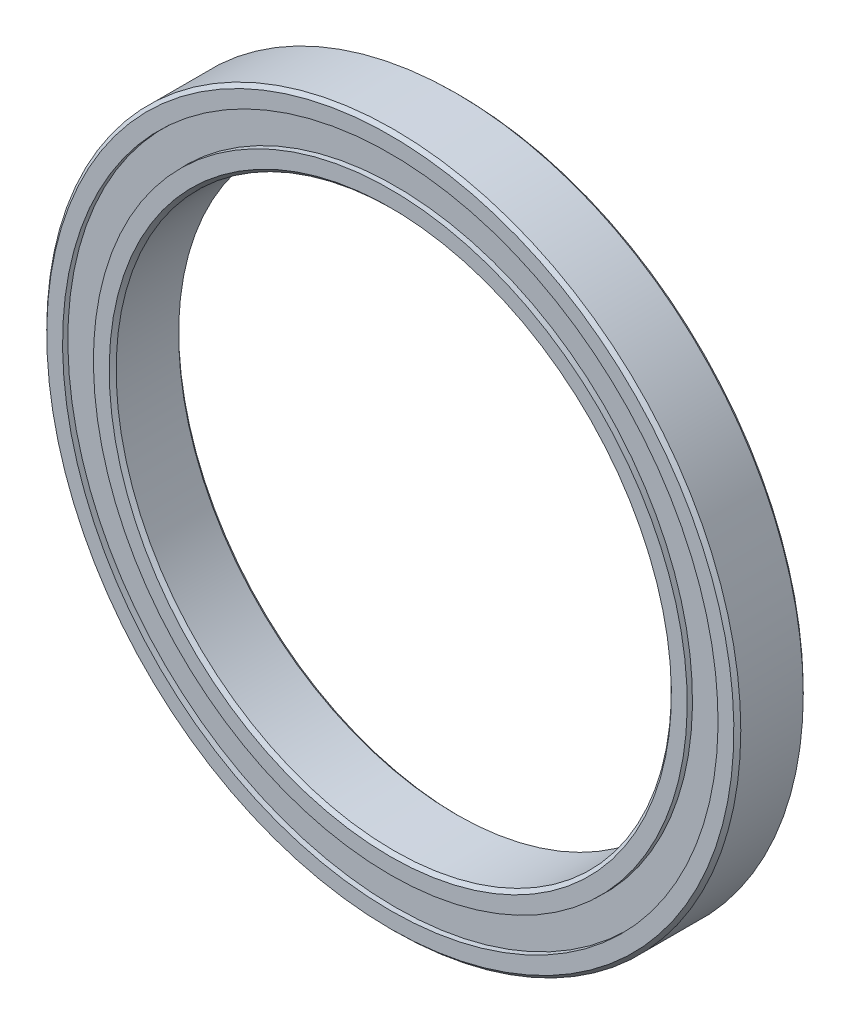
SolidWorks part; units mm, degrees
ref_plane "Front Plane" through (0, 0, 0) normal (0, 0, 1) x (1, 0, 0)
ref_plane "Top Plane" through (0, 0, 0) normal (0, 1, 0) x (1, 0, 0)
ref_plane "Right Plane" through (0, 0, 0) normal (1, 0, 0) x (0, 0, -1)
sketch "Sketch1" plane through (0, 0, 0) normal (0, 0, 1) x (1, 0, 0)
  circle A0 centre (0, 0) radius 50
  circle A1 centre (0, 0) radius 40
  dimension "OD" = 100
  dimension "ID" = 80
  dimension "For Shaft Diameter" = 80
  dimension "For Housing ID" = 100
sketch "Sketch8" plane through (0, 0, 0) normal (1, 0, 0) x (0, 0, -1)
  line L1 (-5, 50) -> (5, 50)
  line L2 (-5, 50) -> (-5, -50)
  line L3 (-5, -50) -> (5, -50)
  line L4 (5, 50) -> (5, -50)
  line L5 (-5, 50) -> (5, -50) construction
  line L6 (-5, -50) -> (5, 50) construction
  point P0 (0, 0)
  point P6 (0, -50)
  dimension "Width" = 10
sketch "Sketch5" plane through (0, 0, 0) normal (1, 0, 0) x (0, 0, -1)
  line L0 (-5, 0) -> (5, 0) construction
  line L1 (0, 50) -> (0, -50) construction
  line L2 (4.5, 50) -> (-4.5, 50)
  line L3 (-4.5, 50) -> (-5, 49.5)
  line L4 (-5, 49.5) -> (-5, 47.2222)
  line L5 (-5, 47.2222) -> (-2.2222, 47.2222)
  line L6 (5, 47.2222) -> (2.2222, 47.2222)
  line L7 (5, 49.5) -> (5, 47.2222)
  line L8 (4.5, 50) -> (5, 49.5)
  line L9 (0, 50) -> (0, 45) construction
  line L10 (0, 45) -> (0, 40) construction
  line L11 (-3.1427, 45) -> (-5, 45) construction
  line L12 (3.8808, 42.8032) -> (4.2618, 42.8032)
  line L13 (-3.8808, 42.8032) -> (-4.2618, 42.8032)
  line L14 (-3.8808, 42.8032) -> (-3.8808, 47.1968)
  line L15 (-3.8808, 47.1968) -> (-4.2618, 47.1968)
  line L16 (-4.2618, 42.8032) -> (-4.2618, 47.1968)
  line L17 (-3.8808, 42.8032) -> (-4.2618, 47.1968) construction
  line L18 (-3.8808, 47.1968) -> (-4.2618, 42.8032) construction
  line L19 (4.2618, 42.8032) -> (4.2618, 47.1968)
  line L20 (3.8808, 47.1968) -> (4.2618, 47.1968)
  line L21 (3.8808, 42.8032) -> (3.8808, 47.1968)
  line L22 (0, 50) -> (0, -50) construction
  line L23 (5, 0) -> (5, 50) construction
  line L24 (5, 50) -> (4.5, 50) construction
  line L25 (-5, 0) -> (-5, 50) construction
  line L26 (-5, 50) -> (-4.5, 50) construction
  line L27 (5, 0) -> (5, -50) construction
  line L28 (-5, 0) -> (-5, -50) construction
  line L29 (-5, -50) -> (5, -50) construction
  arc A0 (-2.2222, 47.2222) -> (2.2222, 47.2222) centre (0, 45) cw
  circle A1 centre (0, 45) radius 3.1427 construction
  point P14 (0, 40)
  point P15 (-4.0713, 45)
  dimension "D1" = 45
  dimension "D2" = 0.5
  dimension "D3" = 4.4444
  dimension "D4" = 2.2222
  dimension "D5" = 0.381
  dimension "D6" = 0.0254
revolve "Revolve1" add sketch "Sketch5" angle 360 about L0
sketch "Sketch3" plane through (0, 0, 0) normal (1, 0, 0) x (0, 0, -1)
  line L0 (-5, 42.7778) -> (-2.2222, 42.7778)
  line L1 (0, 50) -> (0, -50) construction
  line L2 (-5, 49.5) -> (-5, 47.2222) construction
  line L3 (-5, 42.7778) -> (-5, 40.5)
  line L4 (-4.5, 50) -> (-5, 49.5) construction
  line L5 (-5, 40.5) -> (-4.5, 40)
  line L6 (-4.5, 40) -> (4.5, 40)
  line L7 (4.5, 50) -> (4.5, -50) construction
  line L8 (4.5, 40) -> (5, 40.5)
  line L9 (5, -49.5) -> (5, 49.5) construction
  line L10 (5, 40.5) -> (5, 42.7778)
  line L11 (5, 42.7778) -> (2.2222, 42.7778)
  line L13 (4.5, 50) -> (5, 49.5) construction
  arc A0 (2.2222, 47.2222) -> (-2.2222, 47.2222) centre (0, 45) ccw construction
  arc A1 (2.2222, 42.7778) -> (-2.2222, 42.7778) centre (0, 45) cw
revolve "Revolve3" add sketch "Sketch3" angle 360 about L0
sketch "Sketch4" plane through (0, 0, 0) normal (1, 0, 0) x (0, 0, -1)
  line L0 (-3.1427, 45) -> (3.1427, 45)
  arc A2 (-3.1427, 45) -> (3.1427, 45) centre (0, 45) cw
  arc A3 (2.2222, 47.2222) -> (-2.2222, 47.2222) centre (0, 45) ccw construction
revolve "Revolve4" add sketch "Sketch4" angle 360 about L0
pattern_circular "CirPattern1" count 27 every 13.333 about axis through (0, 0, 0) along (0, 0, 1) of bodies 104
equation "\"D2@Sketch5\" = \"Width@Sketch8\" * .05"
equation "\"D3@Sketch5\" = \"Width@Sketch8\" / 2.25"
equation "\"D4@Sketch5\"=((\"OD@Sketch1\"-\"ID@Sketch1\")/2)/4.5"
equation "\"D2@CirPattern1\" = 360/\"Balls@CirPattern1\""
